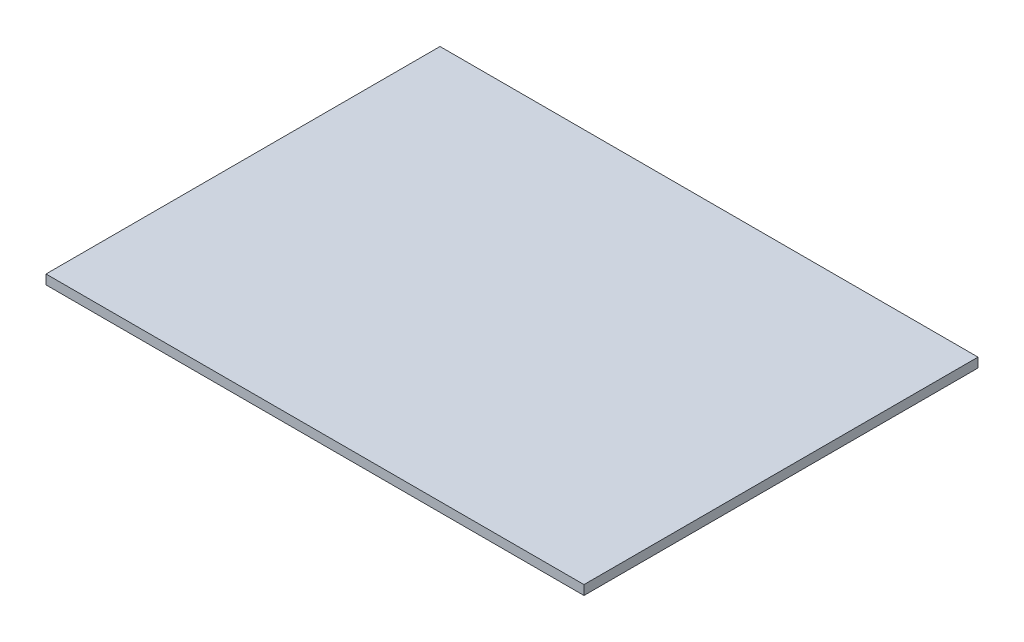
SolidWorks part; units mm, degrees
material "Rubber"
ref_plane "Front Plane" through (0, 0, 0) normal (0, 0, 1) x (1, 0, 0)
ref_plane "Top Plane" through (0, 0, 0) normal (0, 1, 0) x (1, 0, 0)
ref_plane "Right Plane" through (0, 0, 0) normal (1, 0, 0) x (0, 0, -1)
sketch "Sketch2" plane through (0, 0, 0) normal (0, 1, 0) x (1, 0, 0)
  line L2 (-45.085, -33.02) -> (45.085, -33.02)
  line L3 (-45.085, -33.02) -> (-45.085, 33.02)
  line L4 (-45.085, 33.02) -> (45.085, 33.02)
  line L5 (45.085, -33.02) -> (45.085, 33.02)
  line L6 (-45.085, -33.02) -> (45.085, 33.02) construction
  line L7 (-45.085, 33.02) -> (45.085, -33.02) construction
  point P0 (0, 0)
  dimension "D1" = 90.17
  dimension "D2" = 66.04
extrude "Boss-Extrude1" add sketch "Sketch2" along normal blind 1.5875
